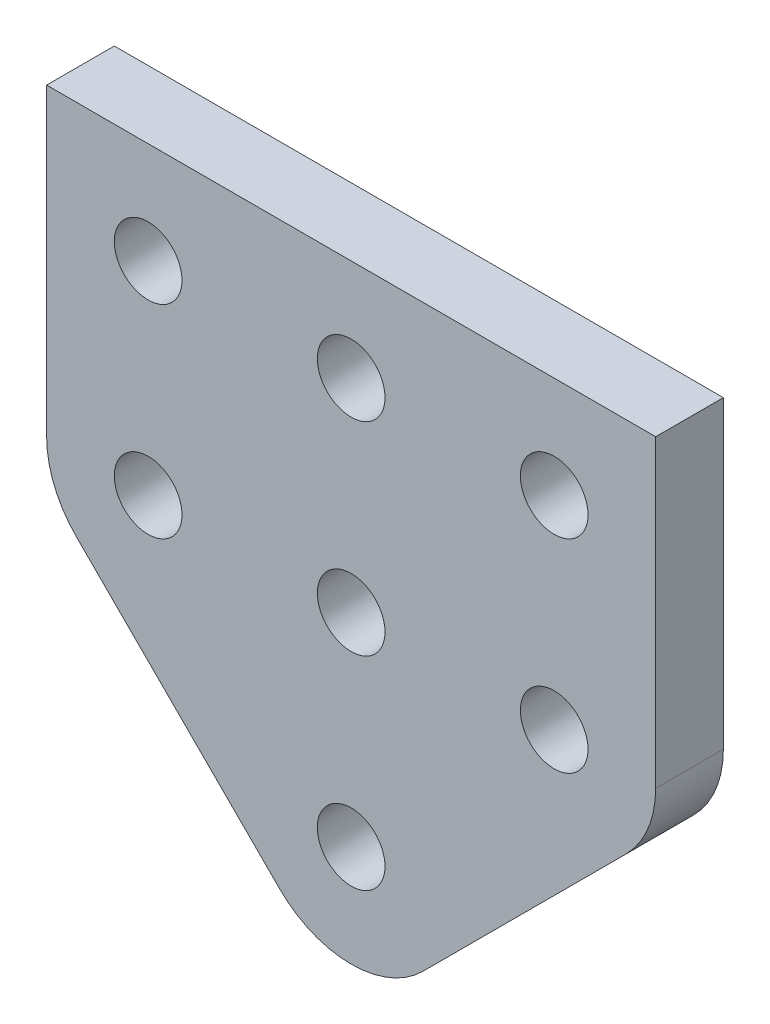
SolidWorks part; units mm, degrees
ref_plane "Alzado" through (0, 0, 0) normal (0, 0, 1) x (1, 0, 0)
ref_plane "Planta" through (0, 0, 0) normal (0, 1, 0) x (1, 0, 0)
ref_plane "Vista lateral" through (0, 0, 0) normal (1, 0, 0) x (0, 0, -1)
sketch "Model" plane through (0, 0, 0) normal (0, 0, 1) x (1, 0, 0)
  line L0 (174.2271, 213.1787) -> (174.2271, 204.1787)
  line L1 (201.2271, 217.6787) -> (174.2271, 217.6787)
  line L2 (174.2271, 213.1787) -> (174.2271, 217.6787)
  line L3 (201.2271, 217.6787) -> (201.2271, 204.1787)
  line L4 (190.909, 191.9967) -> (199.909, 200.9967)
  line L5 (184.5451, 191.9967) -> (175.5451, 200.9967)
  circle A0 centre (187.7271, 204.1787) radius 1.5
  circle A1 centre (178.7271, 204.1787) radius 1.5
  circle A2 centre (187.7271, 213.1787) radius 1.5
  circle A3 centre (178.7271, 213.1787) radius 1.5
  circle A4 centre (196.7271, 213.1787) radius 1.5
  circle A5 centre (187.7271, 195.1787) radius 1.5
  circle A6 centre (196.7271, 204.1787) radius 1.5
  arc A7 (184.5451, 191.9967) -> (190.909, 191.9967) centre (187.7271, 195.1787) ccw
  arc A8 (199.909, 200.9967) -> (201.2271, 204.1787) centre (196.7271, 204.1787) ccw
  arc A9 (174.2271, 204.1787) -> (175.5451, 200.9967) centre (178.7271, 204.1787) ccw
extrude "Saliente-Extruir1" add sketch "Model" along normal blind 3
